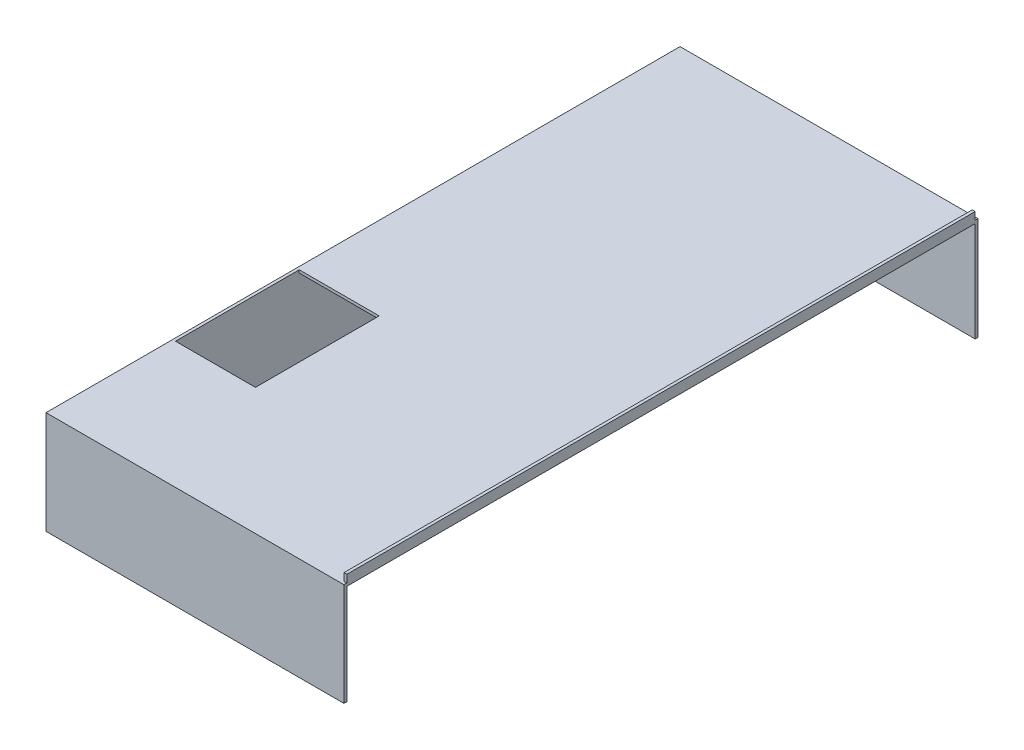
SolidWorks part; units mm, degrees
ref_plane "Front Plane" through (0, 0, 0) normal (0, 0, 1) x (1, 0, 0)
ref_plane "Top Plane" through (0, 0, 0) normal (0, 1, 0) x (1, 0, 0)
ref_plane "Right Plane" through (0, 0, 0) normal (1, 0, 0) x (0, 0, -1)
sketch "Sketch4" plane through (0, 0, 0) normal (0, 1, 0) x (1, 0, 0)
  line L0 (189.3737, 330) -> (344.3737, 330)
  line L1 (344.3737, 330) -> (344.3737, 0)
  line L2 (344.3737, 0) -> (189.3737, 0)
  line L3 (189.3737, 0) -> (189.3737, 65)
  line L4 (189.3737, 65) -> (231.3737, 65)
  line L5 (231.3737, 65) -> (231.3737, 130)
  line L6 (231.3737, 130) -> (189.3737, 130)
  line L7 (189.3737, 130) -> (189.3737, 330)
  point P3 (0, 0)
  dimension "D2" = 200
  dimension "D3" = 42
  dimension "D4" = 65
  dimension "D5" = 155
  dimension "D6" = 155
extrude "Boss-Extrude4" add sketch "Sketch4" along normal blind 1.5 separate body
sketch "Sketch5" plane through (0, 0, 0) normal (0, 0, 1) x (1, 0, 0)
  line L1 (189.3737, 1.5) -> (344.3737, 1.5)
  line L2 (189.3737, 1.5) -> (189.3737, -52.5)
  line L3 (189.3737, -52.5) -> (344.3737, -52.5)
  line L4 (344.3737, 1.5) -> (344.3737, -52.5)
  dimension "D1" = 54
sketch "Sketch7" plane through (0, 0, -330) normal (0, 0, -1) x (-1, 0, 0)
  line L1 (-189.3737, 1.5) -> (-344.3737, 1.5)
  line L2 (-189.3737, 1.5) -> (-189.3737, -52.5)
  line L3 (-189.3737, -52.5) -> (-344.3737, -52.5)
  line L4 (-344.3737, 1.5) -> (-344.3737, -52.5)
  dimension "D1" = 54
sketch "Sketch8" plane through (0, 1.5, 0) normal (0, 1, 0) x (1, 0, 0)
  line L0 (189.3737, 330) -> (344.3737, 330) construction
  line L1 (344.3737, 0) -> (342.8737, 0)
  line L2 (344.3737, 0) -> (344.3737, 330)
  line L3 (344.3737, 330) -> (342.8737, 330)
  line L4 (342.8737, 0) -> (342.8737, 330)
  dimension "D1" = 1.5
extrude "Boss-Extrude5" add sketch "Sketch5" along normal blind 1.5
extrude "Boss-Extrude14" add sketch "Sketch8" along normal blind 4
extrude "Boss-Extrude18" add sketch "Sketch7" along normal blind 1.5
sketch "Sketch9" plane through (189.3737, 0, 0) normal (-1, 0, 0) x (0, 0, 1)
  line L1 (-331.5, 1.5) -> (1.5, 1.5)
  line L2 (-331.5, 1.5) -> (-331.5, -52.5)
  line L3 (-331.5, -52.5) -> (1.5, -52.5)
  line L4 (1.5, 1.5) -> (1.5, -52.5)
extrude "Boss-Extrude19" add sketch "Sketch9" along normal blind 1.5
